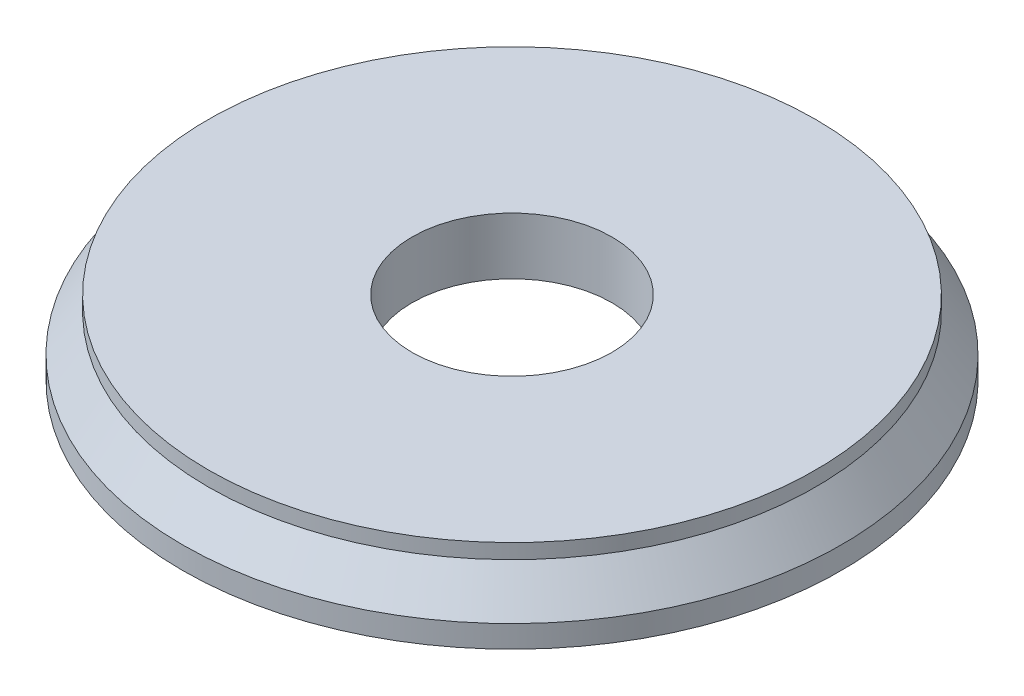
SolidWorks part; units mm, degrees
ref_plane "Плоскость1" through (0, 0, 0) normal (0, 0, 1) x (1, 0, 0)
ref_plane "Плоскость2" through (0, 0, 0) normal (0, 1, 0) x (1, 0, 0)
ref_plane "Плоскость3" through (0, 0, 0) normal (1, 0, 0) x (0, 0, -1)
sketch "Эскиз1" plane through (0, 0, 0) normal (0, 0, 1) x (1, 0, 0)
  line L0 (0, 0) -> (0, 91.3423) construction
  line L1 (13.5, 0) -> (44.5, 0)
  line L2 (44.5, 0) -> (44.5, 3)
  line L3 (44.5, 3) -> (41, 8)
  line L4 (41, 10) -> (41, 8)
  line L5 (41, 10) -> (13.5, 10)
  line L6 (13.5, 0) -> (13.5, 10)
  dimension "D1" = 27
  dimension "D2" = 82
  dimension "D3" = 89
  dimension "D4" = 3
  dimension "D5" = 10
  dimension "D6" = 2
revolve "Повернуть1" add sketch "Эскиз1" angle 360 about L0
chamfer "Фаска1" distance 4 angle 30 1 edges at (0, 0, -13.5)
